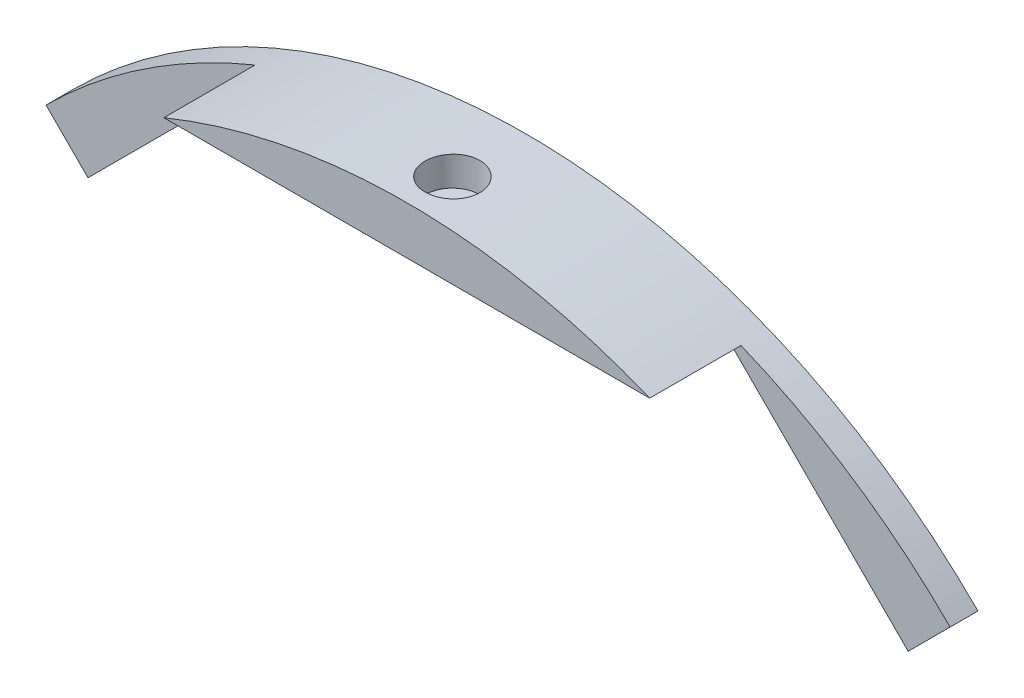
SolidWorks part; units mm, degrees
ref_plane "Front Plane" through (0, 0, 0) normal (0, 0, 1) x (1, 0, 0)
ref_plane "Top Plane" through (0, 0, 0) normal (0, 1, 0) x (1, 0, 0)
ref_plane "Right Plane" through (0, 0, 0) normal (1, 0, 0) x (0, 0, -1)
sketch "Sketch1" plane through (0, 0, 0) normal (0, 0, 1) x (1, 0, 0)
  line L0 (0, 284.5128) -> (0, -315.9314) construction
  line L1 (-464.297, 0) -> (544.589, 0) construction
  line L2 (-129.5, 50.1051) -> (-50.1051, 129.5)
  line L9 (-129.5, 50.1051) -> (-129.5, -50.1051)
  line L11 (-50.1051, -129.5) -> (50.1051, -129.5)
  line L13 (129.5, -50.1051) -> (129.5, 50.1051)
  line L15 (50.1051, 129.5) -> (-50.1051, 129.5)
  line L17 (50.1051, 129.5) -> (129.5, 50.1051)
  line L18 (129.5, -50.1051) -> (50.1051, -129.5)
  line L19 (-50.1051, -129.5) -> (-129.5, -50.1051)
  line L20 (-53.6407, 129.5) -> (-91.5703, 91.5703)
  line L21 (-91.5703, -91.5703) -> (-53.6407, -129.5)
  line L22 (53.6407, -129.5) -> (91.5703, -91.5703)
  line L23 (129.5, 53.6407) -> (91.5703, 91.5703)
  circle A0 centre (0, 0) radius 129.5 construction
  circle A2 centre (0, 0) radius 129.5
  circle A3 centre (0, 0) radius 109.75
  dimension "D2" = 259
  dimension "D3" = 219.5
  dimension "D1" = 0
  dimension "D4" = 259
  dimension "D5" = 254
  dimension "D6" = 4
sketch "Sketch2" plane through (0, 0, 0) normal (0, 0, 1) x (1, 0, 0)
  circle A2 centre (0, 0) radius 109.75
  circle A3 centre (0, 0) radius 129.5
  point P1 (114.75, 0)
  point P3 (0, 0)
  point P9 (104.9544, 32.0878)
  dimension "D1" = 219.5
  dimension "D2" = 259
sketch "Sketch3" plane through (0, 0, 0) normal (0, 0, 1) x (1, 0, 0)
  line L0 (0, 216.6703) -> (0, -179.3029) construction
  line L2 (0, 284.5128) -> (0, -315.9314) construction
  line L4 (-261.0178, 0) -> (186.7113, 0) construction
  line L5 (-464.297, 0) -> (544.589, 0) construction
  line L22 (-157.8941, 129.5) -> (159.8749, 129.5) construction
  line L23 (0, 0) -> (0, 188.0938) construction
  line L40 (-94.2678, 129.5) -> (106.7846, 129.5) construction
  line L41 (129.5, -10) -> (109.5, -10)
  line L42 (10, 129.5) -> (-10, 129.5)
  line L43 (10, 129.5) -> (10, 109.5)
  line L44 (10, 109.5) -> (-10, 109.5)
  line L45 (-10, 129.5) -> (-10, 109.5)
  line L46 (129.5, -10) -> (129.5, 10)
  line L47 (129.5, 10) -> (109.5, 10)
  line L48 (109.5, -10) -> (109.5, 10)
  line L49 (-10, -129.5) -> (-10, -109.5)
  line L50 (-10, -129.5) -> (10, -129.5)
  line L51 (10, -129.5) -> (10, -109.5)
  line L52 (-10, -109.5) -> (10, -109.5)
  line L53 (-129.5, 10) -> (-109.5, 10)
  line L54 (-129.5, 10) -> (-129.5, -10)
  line L55 (-129.5, -10) -> (-109.5, -10)
  line L56 (-109.5, 10) -> (-109.5, -10)
  line L57 (-22.9682, 119.5) -> (92.755, 119.5) construction
  circle A8 centre (-15, 119.5) radius 2.75
  circle A9 centre (15, 119.5) radius 2.75
  circle A10 centre (119.5, 15) radius 2.75
  circle A11 centre (119.5, -15) radius 2.75
  circle A12 centre (15, -119.5) radius 2.75
  circle A13 centre (-15, -119.5) radius 2.75
  circle A14 centre (-119.5, -15) radius 2.75
  circle A15 centre (-119.5, 15) radius 2.75
  dimension "D8" = 5.5
  dimension "D9" = 15
  dimension "D1" = 129.5
  dimension "D2" = 0
  dimension "D3" = 90
  dimension "D4" = 129.5
  dimension "D5" = 20
  dimension "D7" = 10
  dimension "D6" = 20
  dimension "D10" = 10
  dimension "D12" = 4
  dimension "D11" = 4
sketch "Sketch5" plane through (0, 0, 0) normal (0, 0, 1) x (1, 0, 0)
  line L0 (0, 161.9102) -> (0, -158.9824) construction
  line L1 (0, 284.5128) -> (0, -315.9314) construction
  line L11 (-129.5, 50.1051) -> (-50.1051, 129.5) construction
  line L12 (50.1051, 129.5) -> (-50.1051, 129.5) construction
  line L13 (50.1051, 129.5) -> (129.5, 50.1051) construction
  line L14 (-89.8026, 89.8026) -> (-50.1051, 129.5)
  line L15 (50.1051, 129.5) -> (-50.1051, 129.5)
  line L16 (50.1051, 129.5) -> (89.8026, 89.8026)
  line L17 (89.8026, 89.8026) -> (98.9949, 98.9949)
  line L18 (-89.8026, 89.8026) -> (-98.9949, 98.9949)
  arc A5 (98.9949, 98.9949) -> (-98.9949, 98.9949) centre (0, 0) ccw
  dimension "D2" = 280
extrude "Boss-Extrude4" add sketch "Sketch5" against normal blind 6.1
sketch "Sketch6" plane through (0, 0, 0) normal (0, 0, 1) x (1, 0, 0)
  line L0 (0, 241.6622) -> (0, -32.8434) construction
  line L1 (0, 284.5128) -> (0, -315.9314) construction
  line L2 (0, 129.5) -> (-53.1954, 129.5)
  line L3 (50.1051, 129.5) -> (-50.1051, 129.5) construction
  line L4 (0, 129.5) -> (53.1954, 129.5)
  line L5 (-157.8941, 129.5) -> (159.8749, 129.5) construction
  arc A0 (98.9949, 98.9949) -> (-98.9949, 98.9949) centre (0, 0) ccw construction
  arc A1 (53.1954, 129.5) -> (-53.1954, 129.5) centre (0, 0) ccw
extrude "Boss-Extrude5" add sketch "Sketch6" along normal blind 20
sketch "Sketch7" plane through (0, 129.5, 0) normal (0, -1, 0) x (1, 0, 0)
  line L0 (0, 36.651) -> (0, -27.6042) construction
  line L1 (-53.1954, 20) -> (53.1954, 20) construction
  circle A0 centre (0, 10) radius 2.75
  dimension "D1" = 5.5
  dimension "D2" = 10
extrude "Cut-Extrude1" cut sketch "Sketch7" against normal through all
ref_plane "Plane1" through (0, 133.5, 0) normal (0, -1, 0) x (-1, 0, 0)
sketch "Sketch8" plane through (0, 133.5, 0) normal (0, -1, 0) x (-1, 0, 0)
  circle A0 centre (0, -10) radius 6
  dimension "D1" = 12
extrude "Cut-Extrude2" cut sketch "Sketch8" against normal blind 20
